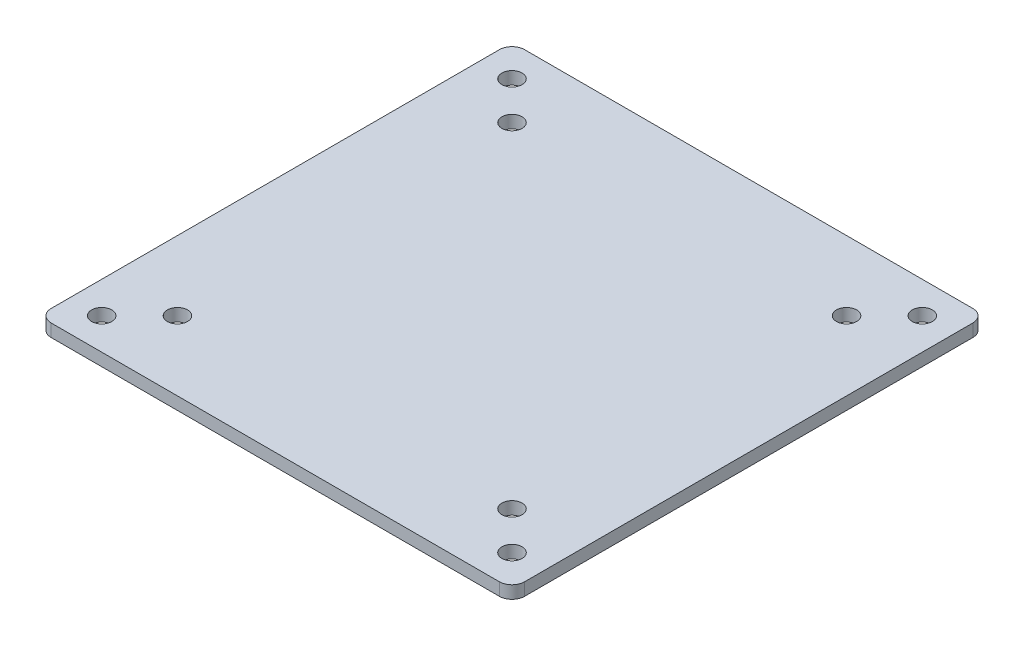
SolidWorks part; units mm, degrees
ref_plane "前视基准面" through (0, 0, 0) normal (0, 0, 1) x (1, 0, 0)
ref_plane "上视基准面" through (0, 0, 0) normal (0, 1, 0) x (1, 0, 0)
ref_plane "右视基准面" through (0, 0, 0) normal (1, 0, 0) x (0, 0, -1)
sketch "草图1" plane through (0, 0, 0) normal (0, 1, 0) x (1, 0, 0)
  line L0 (0, 0) -> (84.7468, 0) construction
  line L1 (-37.5, 37.5) -> (37.5, 37.5)
  line L2 (-37.5, 37.5) -> (-37.5, -37.5)
  line L3 (-37.5, -37.5) -> (37.5, -37.5)
  line L4 (37.5, 37.5) -> (37.5, -37.5)
  line L5 (-37.5, 37.5) -> (37.5, -37.5) construction
  line L6 (-37.5, -37.5) -> (37.5, 37.5) construction
  line L7 (-26.5, 26.5) -> (26.5, 26.5) construction
  line L8 (-26.5, 26.5) -> (-26.5, -26.5) construction
  line L9 (-26.5, -26.5) -> (26.5, -26.5) construction
  line L10 (26.5, 26.5) -> (26.5, -26.5) construction
  line L11 (-26.5, 26.5) -> (26.5, -26.5) construction
  line L12 (-26.5, -26.5) -> (26.5, 26.5) construction
  line L14 (-32.5, 32.5) -> (32.5, 32.5) construction
  line L15 (-32.5, 32.5) -> (-32.5, -32.5) construction
  line L16 (-32.5, -32.5) -> (32.5, -32.5) construction
  line L17 (32.5, 32.5) -> (32.5, -32.5) construction
  line L18 (-32.5, 32.5) -> (32.5, -32.5) construction
  line L19 (-32.5, -32.5) -> (32.5, 32.5) construction
  circle A0 centre (-26.5, 26.5) radius 1.6
  circle A1 centre (26.5, 26.5) radius 1.6
  circle A2 centre (26.5, -26.5) radius 1.6
  circle A3 centre (-26.5, -26.5) radius 1.6
  circle A4 centre (-32.5, 32.5) radius 1.6
  circle A5 centre (32.5, 32.5) radius 1.6
  circle A6 centre (32.5, -32.5) radius 1.6
  circle A7 centre (-32.5, -32.5) radius 1.6
  point P0 (0, 0)
  point P6 (0, 0)
  dimension "D5" = 3.2
  dimension "D6" = 3.2
  dimension "D9" = 3.2
  dimension "D10" = 3.2
  dimension "D1" = 75
  dimension "D2" = 75
  dimension "D3" = 53
  dimension "D4" = 53
  dimension "D7" = 65
  dimension "D8" = 65
extrude "凸台-拉伸1" add sketch "草图1" along normal blind 2
fillet "圆角1" radius 2 4 edges at (-37.5, 1, -37.5) (37.5, 1, -37.5) (37.5, 1, 37.5) (-37.5, 1, 37.5)
